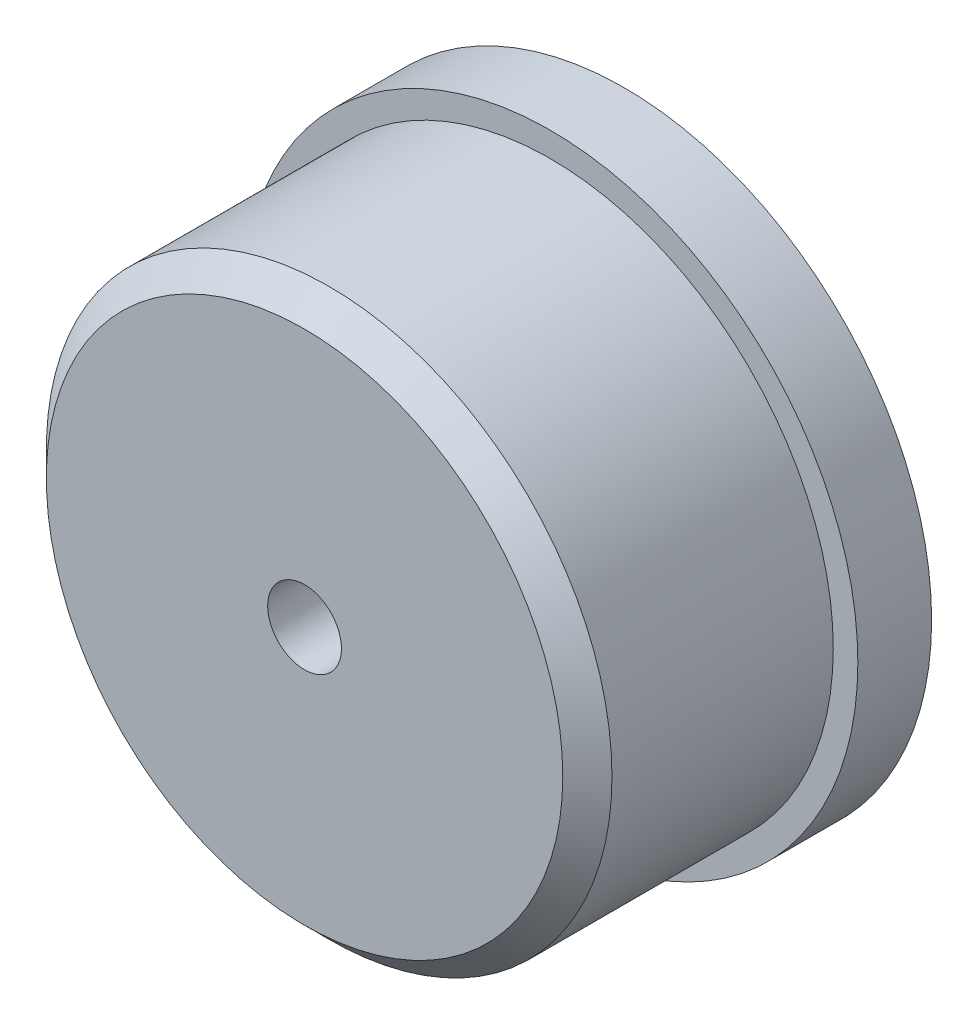
SolidWorks part; units mm, degrees
ref_plane "Plan de face" through (0, 0, 0) normal (0, 0, 1) x (1, 0, 0)
ref_plane "Plan de dessus" through (0, 0, 0) normal (0, 1, 0) x (1, 0, 0)
ref_plane "Plan de droite" through (0, 0, 0) normal (1, 0, 0) x (0, 0, -1)
sketch "Esquisse1" plane through (0, 0, 0) normal (0, 0, 1) x (1, 0, 0)
  circle A0 centre (0, 0) radius 12.5
  dimension "D1" = 25
extrude "Extrusion1" add sketch "Esquisse1" along normal blind 3
sketch "Esquisse2" plane through (0, 0, 3) normal (0, 0, 1) x (1, 0, 0)
  circle A0 centre (0, 0) radius 11.5
  dimension "D1" = 23
extrude "Extrusion2" add sketch "Esquisse2" along normal blind 10
chamfer "Chanfrein1" distance 1 angle 45 1 edges at (11.5, 0, 13)
hole_wizard "Trou taraudé M41" positions "Esquisse4" profile "Esquisse3" tap size "M4" standard "ISO" end condition through all
sketch "Esquisse4" plane through (0, 0, 0) normal (0, 0, -1) x (-1, 0, 0)
  point P0 (0, 0)
sketch "Esquisse3" plane through (0, 0, 0) normal (1, 0, 0) x (0, 1, 0)
  line L0 (0, 0) -> (0, 13)
  line L1 (0, 13) -> (1.5, 13)
  line L2 (1.5, 13) -> (1.5, 0)
  line L5 (1.5, 0) -> (0, 0)
  line L11 (0, -6.35) -> (0, 107.95) construction
  dimension "Diamètre du trou pour taraudage jusqu'au prochain" = 3
  dimension "Profondeur du trou pour taraudage jusqu'au prochain" = 13
cosmetic thread "Filetage de perçage1" parameters "D2"=4
